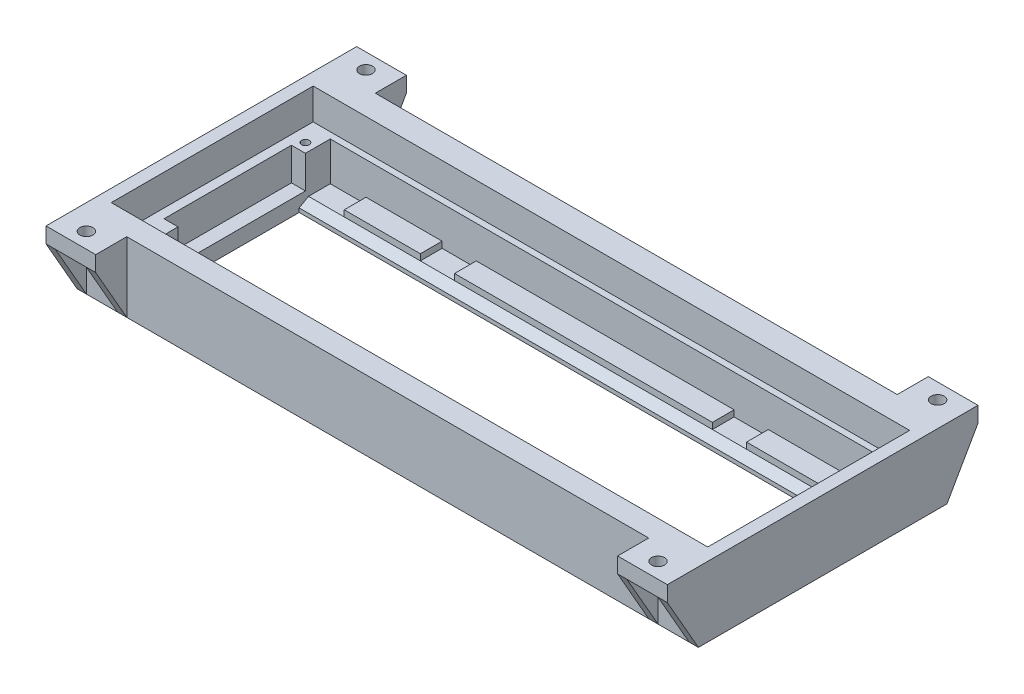
SolidWorks part; units mm, degrees
ref_plane "Спереди" through (0, 0, 0) normal (0, 0, 1) x (1, 0, 0)
ref_plane "Сверху" through (0, 0, 0) normal (0, 1, 0) x (1, 0, 0)
ref_plane "Справа" through (0, 0, 0) normal (1, 0, 0) x (0, 0, -1)
sketch "Эскиз1" plane through (0, 0, 0) normal (0, 1, 0) x (1, 0, 0)
  line L1 (-100, 40) -> (100, 40)
  line L5 (-88.5, 20) -> (88.5, 20)
  line L6 (-100, 40) -> (-100, -40)
  line L7 (-100, -40) -> (100, -40)
  line L8 (100, -40) -> (100, 40)
  line L10 (88.5, 20) -> (88.5, -20)
  line L11 (88.5, -20) -> (-88.5, -20)
  line L12 (-88.5, -20) -> (-88.5, 20)
extrude "Бобышка-Вытянуть1" add sketch "Эскиз1" along normal blind 5
chamfer "Фаска1" distance 3 angle 30 2 edges at (0, 5, 20) (0, 5, -20)
ref_plane "Плоскость4" through (0, 5, 0) normal (0, 1, 0) x (1, 0, 0)
sketch "Эскиз2" plane through (0, 5, 0) normal (0, 1, 0) x (1, 0, 0)
  line L0 (-100, 40) -> (-100, -40)
  line L1 (-100, -40) -> (100, -40)
  line L2 (-100, -40) -> (100, -40) construction
  line L3 (100, -40) -> (100, 40) construction
  line L4 (100, -40) -> (100, 40)
  line L6 (-88.5, 30) -> (-88.5, -28)
  line L7 (88.5, 30) -> (77, 30)
  line L8 (88.5, 30) -> (88.5, -28)
  line L10 (-88.5, 30) -> (-77, 30)
  line L11 (-77, 30) -> (-77, 23)
  line L13 (-88.5, 23) -> (88.5, 23) construction
  line L14 (77, 30) -> (77, 23)
  line L16 (52.5, 23) -> (52.5, 30)
  line L18 (-52.5, 23) -> (-52.5, 30)
  line L19 (-52.5, 30) -> (-41.5, 30)
  line L20 (-41.5, 30) -> (-41.5, 23)
  line L21 (52.5, 30) -> (41.5, 30)
  line L22 (41.5, 30) -> (41.5, 23)
  line L24 (48.5, -28) -> (48.5, -32)
  line L25 (88.5, -28) -> (48.5, -28)
  line L26 (-48.5, -28) -> (-48.5, -32)
  line L27 (-88.5, -28) -> (-48.5, -28)
  line L28 (-48.5, -32) -> (-32.5, -32)
  line L29 (48.5, -32) -> (32.5, -32)
  line L30 (32.5, -32) -> (32.5, -28)
  line L32 (-32.5, -28) -> (-32.5, -32)
  line L33 (-100, 40) -> (100, 40)
  line L36 (-41.5, 23) -> (41.5, 23)
  line L41 (-32.5, -28) -> (32.5, -28)
  line L44 (-77, 23) -> (-52.5, 23)
  line L45 (52.5, 23) -> (77, 23)
extrude "Бобышка-Вытянуть2" add sketch "Эскиз2" along normal blind 2
ref_plane "Плоскость5" through (0, 7, 0) normal (0, 1, 0) x (1, 0, 0)
sketch "Эскиз3" plane through (0, 7, 0) normal (0, 1, 0) x (1, 0, 0)
  line L1 (-100, 40) -> (-100, -40)
  line L6 (100, -40) -> (100, 40)
  line L9 (-93, 22) -> (-88.5, 22)
  line L11 (93, 22) -> (88.5, 22)
  line L29 (-88.5, 30) -> (88.5, 30)
  line L30 (88.5, 30) -> (77, 30) construction
  line L32 (-100, 40) -> (100, 40)
  line L33 (100, -40) -> (-100, -40)
  line L38 (88.5, 22) -> (88.5, 30)
  line L39 (-88.5, 30) -> (-88.5, 22)
  line L40 (93, -19) -> (88.5, -19)
  line L41 (88.5, -28) -> (88.5, 30) construction
  line L42 (-93, -19) -> (-88.5, -19)
  line L43 (-88.5, 30) -> (-88.5, -28) construction
  line L44 (93, 22) -> (93, -19)
  line L45 (-93, 22) -> (-93, -19)
  line L46 (-88.5, -33) -> (88.5, -33)
  line L48 (-88.5, -33) -> (-88.5, -19)
  line L49 (88.5, -33) -> (88.5, -19)
  circle A0 centre (-91.5, 25) radius 1.25
  circle A1 centre (91.5, 25) radius 1.25
  circle A4 centre (-91.5, -27) radius 1.25
  circle A5 centre (91.5, -27) radius 1.25
  point P8 (0, 0)
  point P32 (0, 0)
  point P33 (0, 0)
extrude "Бобышка-Вытянуть3" add sketch "Эскиз3" along normal blind 10.5
ref_plane "Плоскость6" through (0, 17.5, 0) normal (0, 1, 0) x (1, 0, 0)
sketch "Эскиз4" plane through (0, 17.5, 0) normal (0, 1, 0) x (1, 0, 0)
  line L1 (-100, -40) -> (100, -40)
  line L3 (100, 40) -> (-100, 40)
  line L6 (-96, 32) -> (-96, -33)
  line L11 (96, 32) -> (96, -33)
  line L12 (96, -33) -> (-96, -33)
  line L13 (-96, 32) -> (96, 32)
  line L15 (-100, 40) -> (-100, -40)
  line L16 (100, -40) -> (100, 40)
extrude "Бобышка-Вытянуть4" add sketch "Эскиз4" along normal blind 10
chamfer "Фаска2" distance 5 angle 45 4 edges at (-100, 0, 0) (0, 0, 40) (100, 0, 0) (0, 0, -40)
ref_plane "Плоскость7" through (0, 27.5, 0) normal (0, 1, 0) x (1, 0, 0)
sketch "Эскиз6" plane through (0, 27.5, 0) normal (0, 1, 0) x (1, 0, 0)
  line L18 (-100, 40) -> (-100, 50)
  line L19 (-100, 50) -> (-84, 50)
  line L20 (-84, 50) -> (-84, 40)
  line L21 (100, 40) -> (-100, 40) construction
  line L22 (-84, 40) -> (-100, 40)
  line L23 (100, 40) -> (100, 50)
  line L24 (100, 50) -> (84, 50)
  line L25 (84, 50) -> (84, 40)
  line L26 (84, 40) -> (100, 40)
  line L27 (100, -40) -> (100, -50)
  line L28 (100, -50) -> (84, -50)
  line L29 (84, -50) -> (84, -40)
  line L30 (-100, -40) -> (100, -40) construction
  line L31 (84, -40) -> (100, -40)
  line L32 (-100, -40) -> (-100, -50)
  line L33 (-100, -50) -> (-84, -50)
  line L34 (-84, -50) -> (-84, -40)
  line L35 (-84, -40) -> (-100, -40)
  circle A0 centre (-92, 45) radius 2.1
  circle A1 centre (-92, -45) radius 2.1
  circle A2 centre (92, 45) radius 2.1
  circle A3 centre (92, -45) radius 2.1
  point P1 (-90.7963, 45)
  point P4 (-93.3989, -45)
  point P6 (90.5833, 45)
  point P7 (93.1343, -45)
extrude "Бобышка-Вытянуть6" add sketch "Эскиз6" against normal blind 5
ref_plane "Плоскость11" through (100, 0, 0) normal (1, 0, 0) x (0, 0, -1)
sketch "Эскиз10" plane through (100, 0, 0) normal (1, 0, 0) x (0, 0, -1)
  line L0 (-50, 22.5) -> (-40, 5)
  line L1 (-40, 5) -> (-40, 22.5)
  line L2 (-40, 22.5) -> (-50, 22.5)
  line L3 (40, 5) -> (50, 22.5)
  line L4 (50, 22.5) -> (40, 22.5)
  line L5 (40, 22.5) -> (40, 5)
extrude "Бобышка-Вытянуть9" add sketch "Эскиз10" against normal blind 16
ref_plane "Плоскость12" through (-100, 0, 0) normal (-1, 0, 0) x (0, 0, 1)
sketch "Эскиз11" plane through (-100, 0, 0) normal (-1, 0, 0) x (0, 0, 1)
  line L0 (-50, 22.5) -> (-40, 22.5)
  line L1 (-40, 22.5) -> (-40, 5)
  line L2 (-40, 5) -> (-50, 22.5)
  line L3 (40, 5) -> (50, 22.5)
  line L4 (50, 22.5) -> (40, 22.5)
  line L5 (40, 22.5) -> (40, 5)
extrude "Бобышка-Вытянуть10" add sketch "Эскиз11" against normal blind 16
ref_plane "Плоскость13" through (0, 22.5, 0) normal (0, 1, 0) x (1, 0, 0)
sketch "Эскиз12" plane through (0, 22.5, 0) normal (0, 1, 0) x (1, 0, 0)
  line L0 (-97, -50) -> (-87, -50)
  line L2 (-84, 50) -> (-100, 50) construction
  line L3 (-97, 50) -> (-97, 40)
  line L4 (-97, 40) -> (-87, 40)
  line L5 (-87, 40) -> (-87, 50)
  line L6 (-87, 50) -> (-97, 50)
  line L7 (-100, -50) -> (-84, -50) construction
  line L8 (-87, -50) -> (-87, -40)
  line L9 (-87, -40) -> (-97, -40)
  line L10 (-97, -40) -> (-97, -50)
  line L11 (97, 50) -> (87, 50)
  line L12 (84, -50) -> (100, -50) construction
  line L13 (87, -50) -> (87, -40)
  line L14 (87, -40) -> (97, -40)
  line L15 (97, -40) -> (97, -50)
  line L16 (97, -50) -> (87, -50)
  line L17 (100, 50) -> (84, 50) construction
  line L18 (87, 50) -> (87, 40)
  line L19 (87, 40) -> (97, 40)
  line L20 (97, 40) -> (97, 50)
extrude "Вырез-Вытянуть2" cut sketch "Эскиз12" against normal blind 22
chamfer "Фаска3" distance 2 angle 60 4 edges at (88.5, 0, 0) (0, 0, -20) (0, 0, 20) (-88.5, 0, 0)
